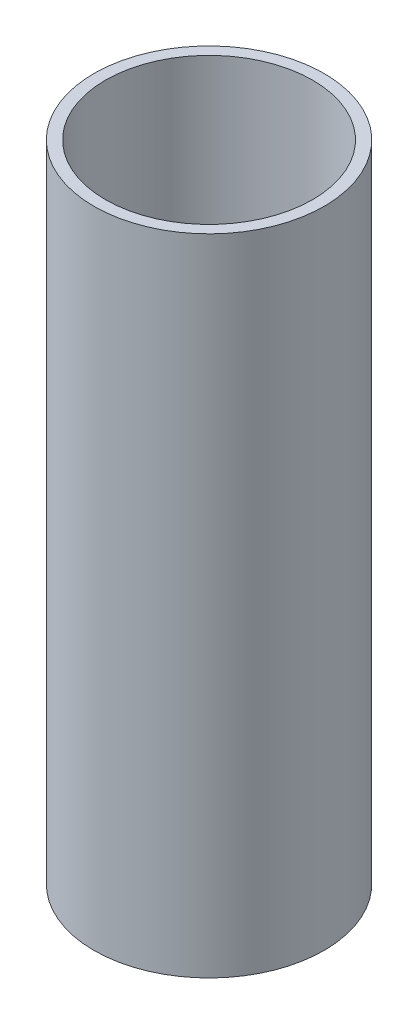
SolidWorks part; units mm, degrees
material "Alloy Steel"
ref_plane "Front Plane" through (0, 0, 0) normal (0, 0, 1) x (1, 0, 0)
ref_plane "Top Plane" through (0, 0, 0) normal (0, 1, 0) x (1, 0, 0)
ref_plane "Right Plane" through (0, 0, 0) normal (1, 0, 0) x (0, 0, -1)
sketch "BaseS" plane through (0, 0, 0) normal (0, 1, 0) x (1, 0, 0)
  circle A0 centre (0, 0) radius 4.5
  circle A1 centre (0, 0) radius 5
  dimension "D1" = 9
  dimension "D2" = 0.5
extrude "BASE" add sketch "BaseS" along normal mid plane 28
